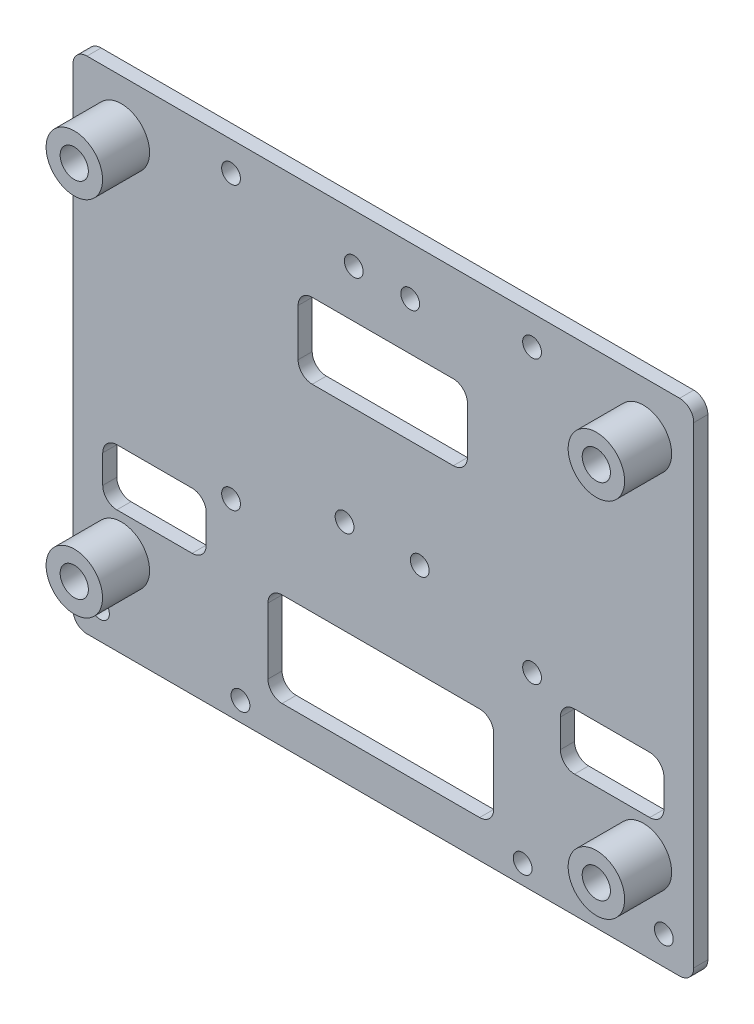
SolidWorks part; units mm, degrees
ref_plane "Front Plane" through (0, 0, 0) normal (0, 0, 1) x (1, 0, 0)
ref_plane "Top Plane" through (0, 0, 0) normal (0, 1, 0) x (1, 0, 0)
ref_plane "Right Plane" through (0, 0, 0) normal (1, 0, 0) x (0, 0, -1)
other "Graphic1"
ref_plane "Plane1" through (0, 0, 10) normal (0, 0, 1) x (1, 0, 0)
sketch "Sketch6" plane through (0, 0, 10) normal (0, 0, 1) x (1, 0, 0)
  line L0 (181.8653, 439.4161) -> (181.8653, 445.9653) construction
  line L1 (146.1138, 438.1792) -> (212.1138, 438.1792)
  line L2 (146.1138, 438.1792) -> (146.1138, 384.9792)
  line L3 (146.1138, 384.9792) -> (212.1138, 384.9792)
  line L4 (212.1138, 438.1792) -> (212.1138, 384.9792)
  circle A12 centre (175.9727, 433.0094) radius 1
  circle A13 centre (181.9727, 433.0094) radius 1
  circle A14 centre (174.9913, 408.9832) radius 1
  circle A15 centre (182.9913, 408.9832) radius 1
  circle A16 centre (162.9269, 435.0502) radius 1
  circle A17 centre (194.9269, 435.0502) radius 1
  circle A18 centre (162.9269, 405.0774) radius 1
  circle A19 centre (194.9269, 405.0774) radius 1
  circle A20 centre (163.9269, 387.0168) radius 1
  circle A21 centre (193.9269, 387.0168) radius 1
  circle A22 centre (148.9902, 388.0168) radius 1
  circle A23 centre (208.9358, 388.0168) radius 1
  dimension "D3" = 6
  dimension "D5" = 32
  dimension "D1" = 66
  dimension "D2" = 53.2
  dimension "D4" = 8
extrude "Boss-Extrude1" add sketch "Sketch6" along normal blind 1.5
sketch "Sketch7" plane through (0, 0, 11.5) normal (0, 0, 1) x (1, 0, 0)
  line L0 (179.1138, 384.9792) -> (179.1138, 381.764) construction
  line L1 (170.0554, 427.9393) -> (188.0554, 427.9393)
  line L2 (170.0554, 427.9393) -> (170.0554, 419.9393)
  line L3 (170.0554, 419.9393) -> (188.0554, 419.9393)
  line L4 (188.0554, 427.9393) -> (188.0554, 419.9393)
  line L5 (166.8507, 398.9443) -> (190.8507, 398.9443)
  line L6 (166.8507, 398.9443) -> (166.8507, 388.9443)
  line L7 (166.8507, 388.9443) -> (190.8507, 388.9443)
  line L8 (190.8507, 398.9443) -> (190.8507, 388.9443)
  line L9 (197.9397, 403.9898) -> (208.9397, 403.9898)
  line L10 (197.9397, 403.9898) -> (197.9397, 397.9898)
  line L11 (197.9397, 397.9898) -> (208.9397, 397.9898)
  line L12 (208.9397, 403.9898) -> (208.9397, 397.9898)
  line L13 (146.1138, 384.9792) -> (212.1138, 384.9792) construction
  line L14 (160.2879, 397.9898) -> (149.2879, 397.9898)
  line L15 (149.2879, 403.9898) -> (149.2879, 397.9898)
  line L16 (160.2879, 403.9898) -> (149.2879, 403.9898)
  line L17 (160.2879, 403.9898) -> (160.2879, 397.9898)
  dimension "D1" = 18
  dimension "D2" = 8
  dimension "D3" = 24
  dimension "D4" = 10
  dimension "D5" = 11
  dimension "D6" = 6
extrude "Cut-Extrude1" cut sketch "Sketch7" against normal blind 1.5
sketch "Sketch8" plane through (0, 0, 11.5) normal (0, 0, 1) x (1, 0, 0)
  circle A0 centre (151.2663, 432.6212) radius 3
  circle A1 centre (206.7663, 432.6212) radius 3
  circle A2 centre (206.7663, 394.1212) radius 3
  circle A3 centre (151.2663, 394.1212) radius 3
  dimension "D1" = 2
  dimension "D2" = 2
extrude "Boss-Extrude2" add sketch "Sketch8" along normal blind 5
fillet "Fillet1" radius 1.5 20 edges at (197.9397, 397.9898, 10.75) (197.9397, 403.9898, 10.75) (208.9397, 403.9898, 10.75) (208.9397, 397.9898, 10.75) (190.8507, 388.9443, 10.75) (190.8507, 398.9443, 10.75) (166.8507, 388.9443, 10.75) (166.8507, 398.9443, 10.75) (160.2879, 397.9898, 10.75) (160.2879, 403.9898, 10.75) (149.2879, 403.9898, 10.75) (149.2879, 397.9898, 10.75) (170.0554, 419.9393, 10.75) (188.0554, 419.9393, 10.75) (188.0554, 427.9393, 10.75) (170.0554, 427.9393, 10.75) (146.1138, 438.1792, 10.75) (146.1138, 384.9792, 10.75) (212.1138, 438.1792, 10.75) (212.1138, 384.9792, 10.75)
sketch "Sketch9" plane through (0, 0, 16.5) normal (0, 0, 1) x (1, 0, 0)
  circle A0 centre (151.258, 432.6382) radius 1.5
  circle A1 centre (206.758, 432.6382) radius 1.5
  circle A2 centre (206.758, 394.1382) radius 1.5
  circle A3 centre (151.258, 394.1382) radius 1.5
  point P2 (161.258, 432.6382)
  dimension "D1" = 2
  dimension "D2" = 2
extrude "Cut-Extrude2" cut sketch "Sketch9" against normal through all
